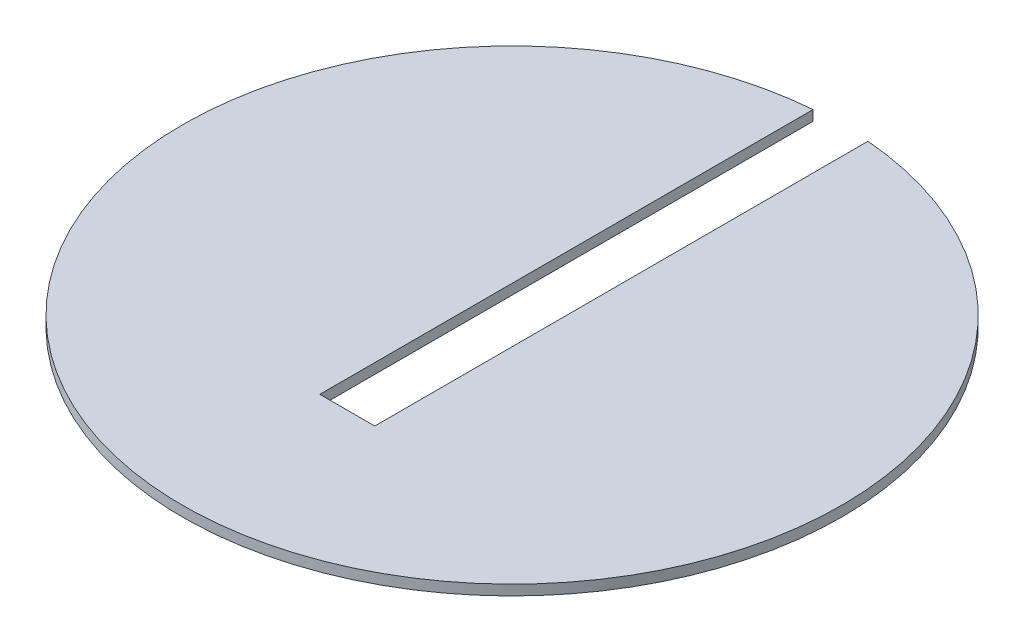
SolidWorks part; units mm, degrees
ref_plane "Ön Düzlem" through (0, 0, 0) normal (0, 0, 1) x (1, 0, 0)
ref_plane "Üst Düzlem" through (0, 0, 0) normal (0, 1, 0) x (1, 0, 0)
ref_plane "Sağ Düzlem" through (0, 0, 0) normal (1, 0, 0) x (0, 0, -1)
sketch "Çizim1" plane through (0, 0, 0) normal (0, 1, 0) x (1, 0, 0)
  line L1 (-7.5, -45) -> (7.5, -45)
  line L2 (-7.5, -45) -> (-7.5, 89.687)
  line L4 (7.5, -45) -> (7.5, 89.687)
  arc A0 (-7.5, 89.687) -> (7.5, 89.687) centre (0, 0) ccw
  dimension "D1" = 180
  dimension "D2" = 15
  dimension "D3" = 7.5
extrude "Yükseklik-Ekstrüzyon1" add sketch "Çizim1" along normal blind 2.8
